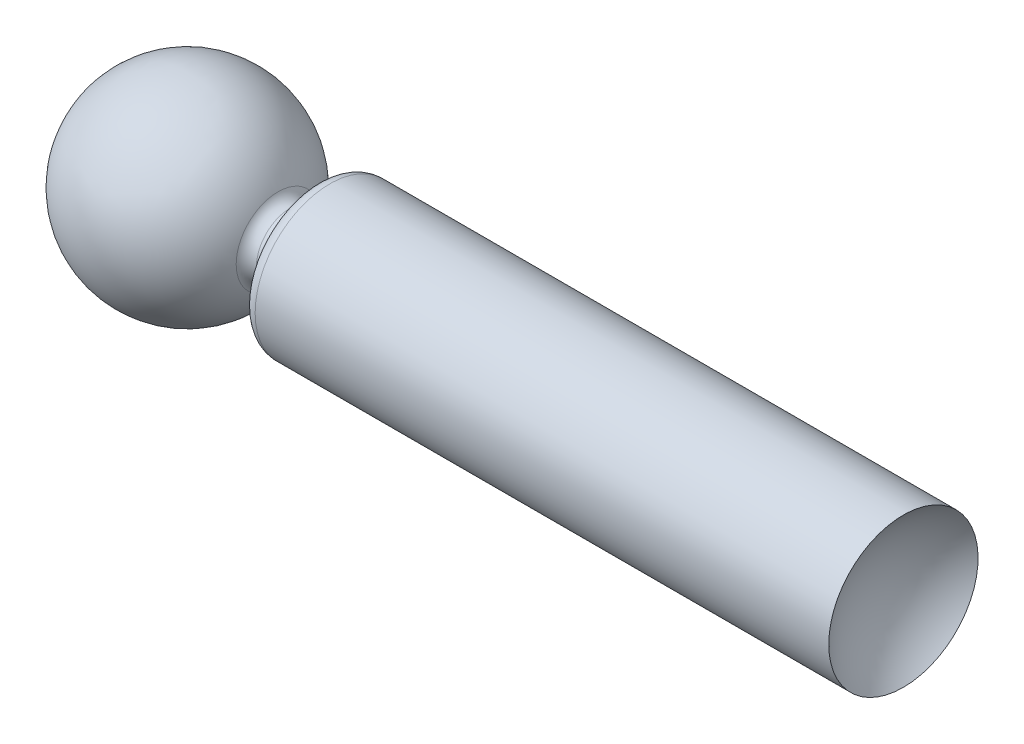
SolidWorks part; units mm, degrees
ref_plane "Front Plane" through (0, 0, 0) normal (0, 0, 1) x (1, 0, 0)
ref_plane "Top Plane" through (0, 0, 0) normal (0, 1, 0) x (1, 0, 0)
ref_plane "Right Plane" through (0, 0, 0) normal (1, 0, 0) x (0, 0, -1)
sketch "Sketch1" plane through (0, 0, 0) normal (0, 0, 1) x (1, 0, 0)
  line L0 (-323.1722, 0) -> (15835.4373, 0) construction
  line L1 (9.6419, 3.175) -> (10.795, 3.175)
  line L2 (12.065, 4.445) -> (12.065, 5.715)
  line L3 (13.335, 6.985) -> (67.0064, 6.985)
  line L4 (63.9572, 0) -> (-9.3472, 0)
  arc A0 (8.4886, 3.9133) -> (-9.3472, 0) centre (0, 0) ccw
  arc A1 (67.0064, 6.985) -> (63.9572, 0) centre (73.4822, 0) ccw
  arc A2 (12.065, 5.715) -> (13.335, 6.985) centre (13.335, 5.715) cw
  arc A3 (10.795, 3.175) -> (12.065, 4.445) centre (10.795, 4.445) ccw
  arc A4 (9.6419, 3.175) -> (8.4886, 3.9133) centre (9.6419, 4.445) cw
  point P15 (12.065, 3.175)
  dimension "D1" = 9.3472
  dimension "D2" = 9.525
  dimension "D6" = 1.27
  dimension "D3" = 6.985
  dimension "D4" = 3.175
  dimension "D5" = 12.065
  dimension "D7" = 63.9572
revolve "Revolve1" add sketch "Sketch1" angle 360 about L0
sketch "Sketch2" plane through (0, 0, 0) normal (0, 1, 0) x (1, 0, 0)
  line L2 (0, 0) -> (50000, 0) construction
  arc A2 (79.0878, -7.7009) -> (81.6141, -11.1714) centre (80.3509, -9.4362) cw
  arc A4 (61.56, -6.985) -> (81.6141, -11.1714) centre (73.4822, 0) ccw
  arc A5 (67.0064, -6.985) -> (79.0878, -7.7009) centre (73.4822, 0) ccw
  point P3 (0, 0)
  dimension "D1" = 13.8177
